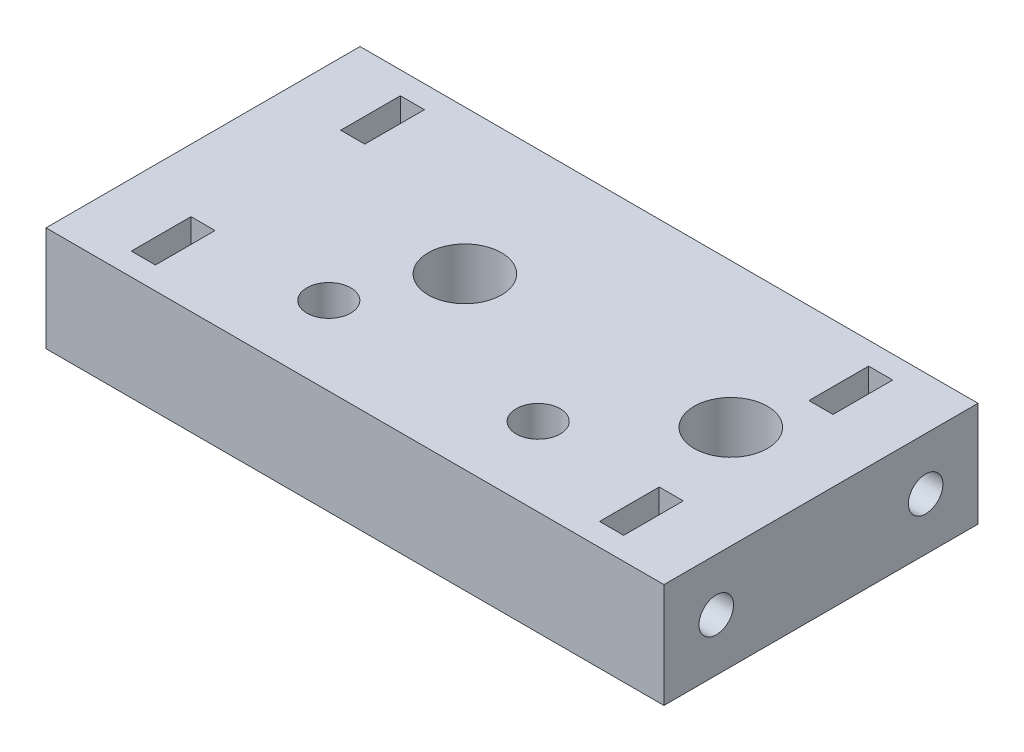
SolidWorks part; units mm, degrees
ref_plane "Front Plane" through (0, 0, 0) normal (0, 0, 1) x (1, 0, 0)
ref_plane "Top Plane" through (0, 0, 0) normal (0, 1, 0) x (1, 0, 0)
ref_plane "Right Plane" through (0, 0, 0) normal (1, 0, 0) x (0, 0, -1)
sketch "Sketch1" plane through (0, 0, 0) normal (0, 1, 0) x (1, 0, 0)
  line L1 (-29.5136, -15) -> (29.5136, -15)
  line L2 (-29.5136, -15) -> (-29.5136, 15)
  line L3 (-29.5136, 15) -> (29.5136, 15)
  line L4 (29.5136, -15) -> (29.5136, 15)
  line L5 (-29.5136, -15) -> (29.5136, 15) construction
  line L6 (-29.5136, 15) -> (29.5136, -15) construction
  point P0 (0, 0)
  dimension "D1" = 59.0272
  dimension "D2" = 30
extrude "Boss-Extrude1" add sketch "Sketch1" along normal blind 10
sketch "Sketch2" plane through (0, 10, 0) normal (0, 1, 0) x (1, 0, 0)
  line L0 (-10, -7.5) -> (10, -7.5) construction
  line L3 (0, 15) -> (0, -15) construction
  line L4 (29.5136, 15) -> (-29.5136, 15) construction
  line L5 (-29.5136, -15) -> (29.5136, -15) construction
  circle A0 centre (-10, -7.5) radius 2.1
  circle A1 centre (10, -7.5) radius 2.1
  point P3 (0, -7.5)
  dimension "D1" = 4.2
  dimension "D2" = 20
  dimension "D3" = 7.5
extrude "Cut-Extrude1" cut sketch "Sketch2" against normal through all
sketch "Sketch3" plane through (29.5136, 0, 0) normal (1, 0, 0) x (0, 0, -1)
  line L0 (0, 10) -> (0, 0) construction
  line L1 (-15, 10) -> (15, 10) construction
  line L2 (-15, 0) -> (15, 0) construction
  line L3 (-10, 5) -> (10, 5) construction
  circle A0 centre (-10, 5) radius 1.65
  circle A1 centre (10, 5) radius 1.65
  point P9 (0, 5)
  dimension "D2" = 3.3
  dimension "D1" = 20
extrude "Cut-Extrude2" cut sketch "Sketch3" against normal blind 12
sketch "Sketch4" plane through (-29.5136, 0, 0) normal (-1, 0, 0) x (0, 0, 1)
  line L0 (0, 10) -> (0, 0) construction
  line L3 (-10, 5) -> (10, 5) construction
  line L4 (-15, 10) -> (15, 10) construction
  circle A0 centre (-10, 5) radius 1.65
  circle A1 centre (10, 5) radius 1.65
  point P9 (0, 5)
  dimension "D2" = 3.3
  dimension "D1" = 20
extrude "Cut-Extrude3" cut sketch "Sketch4" against normal blind 12
ref_plane "Plane1" through (23.5136, 0, 0) normal (1, 0, 0) x (0, 0, -1)
ref_plane "Plane2" through (-23.5136, 0, 0) normal (-1, 0, 0) x (0, 0, 1)
sketch "Sketch5" plane through (23.5136, 0, 0) normal (1, 0, 0) x (0, 0, -1)
  line L0 (-12.85, 6.6454) -> (-12.85, 10)
  line L1 (-7.15, 6.6454) -> (-10, 8.2909) construction
  line L2 (-10, 8.2909) -> (-12.85, 6.6454) construction
  line L3 (-12.85, 6.6454) -> (-12.85, 3.3546)
  line L4 (-12.85, 3.3546) -> (-10, 1.7091)
  line L5 (-10, 1.7091) -> (-7.15, 3.3546)
  line L6 (-7.15, 3.3546) -> (-7.15, 6.6454)
  line L7 (10, 8.2909) -> (7.15, 6.6454) construction
  line L8 (7.15, 6.6454) -> (7.15, 3.3546)
  line L9 (7.15, 3.3546) -> (10, 1.7091)
  line L10 (10, 1.7091) -> (12.85, 3.3546)
  line L11 (12.85, 3.3546) -> (12.85, 6.6454)
  line L12 (12.85, 6.6454) -> (10, 8.2909) construction
  line L13 (-15, 10) -> (15, 10) construction
  line L14 (-12.85, 10) -> (-7.15, 10)
  line L15 (-7.15, 10) -> (-7.15, 6.6454)
  line L16 (7.15, 6.6454) -> (7.15, 10)
  line L17 (7.15, 10) -> (12.85, 10)
  line L18 (12.85, 10) -> (12.85, 6.6454)
  circle A0 centre (-10, 5) radius 2.85 construction
  circle A1 centre (10, 5) radius 2.85 construction
  dimension "D1" = 5.7
extrude "Cut-Extrude4" cut sketch "Sketch5" against normal blind 2.3
sketch "Sketch6" plane through (-23.5136, 0, 0) normal (-1, 0, 0) x (0, 0, 1)
  line L0 (-12.85, 6.6454) -> (-12.85, 10)
  line L1 (-7.15, 6.6454) -> (-10, 8.2909) construction
  line L2 (-10, 8.2909) -> (-12.85, 6.6454) construction
  line L3 (-12.85, 6.6454) -> (-12.85, 3.3546)
  line L4 (-12.85, 3.3546) -> (-10, 1.7091)
  line L5 (-10, 1.7091) -> (-7.15, 3.3546)
  line L6 (-7.15, 3.3546) -> (-7.15, 6.6454)
  line L7 (10, 8.2909) -> (7.15, 6.6454) construction
  line L8 (7.15, 6.6454) -> (7.15, 3.3546)
  line L9 (7.15, 3.3546) -> (10, 1.7091)
  line L10 (10, 1.7091) -> (12.85, 3.3546)
  line L11 (12.85, 3.3546) -> (12.85, 6.6454)
  line L12 (12.85, 6.6454) -> (10, 8.2909) construction
  line L14 (-12.85, 10) -> (-7.15, 10)
  line L15 (-7.15, 10) -> (-7.15, 6.6454)
  line L16 (7.15, 6.6454) -> (7.15, 10)
  line L17 (7.15, 10) -> (12.85, 10)
  line L18 (12.85, 10) -> (12.85, 6.6454)
  line L19 (-15, 10) -> (15, 10) construction
  circle A0 centre (-10, 5) radius 2.85 construction
  circle A1 centre (10, 5) radius 2.85 construction
  circle A2 centre (-10, 5) radius 1.65 construction
  circle A3 centre (-10, 5) radius 1.65 construction
  circle A5 centre (10, 5) radius 1.65 construction
  circle A6 centre (10, 5) radius 1.65 construction
  dimension "D1" = 5.7
extrude "Cut-Extrude5" cut sketch "Sketch6" against normal blind 2.3
sketch "Sketch7" plane through (0, 10, 0) normal (0, 1, 0) x (1, 0, 0)
  line L0 (29.5136, -15) -> (29.5136, 15) construction
  line L1 (-29.5136, -15) -> (29.5136, -15) construction
  line L2 (19.7, 1.2) -> (-5.7, 1.2) construction
  circle A0 centre (19.7, 1.2) radius 3.5
  circle A1 centre (-5.7, 1.2) radius 3.5
  dimension "D3" = 7
  dimension "D1" = 9.8136
  dimension "D2" = 16.2
  dimension "D4" = 25.4
extrude "Cut-Extrude6" cut sketch "Sketch7" against normal through all
